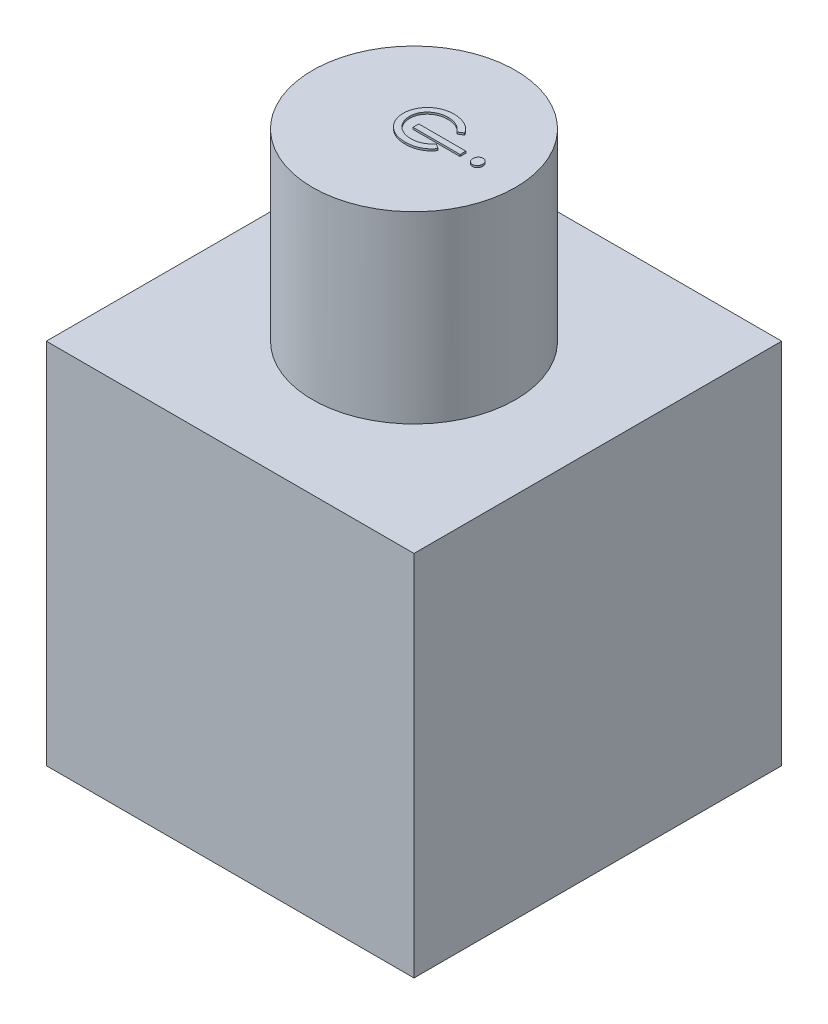
SolidWorks part; units mm, degrees
ref_plane "Front Plane" through (0, 0, 0) normal (0, 0, 1) x (1, 0, 0)
ref_plane "Top Plane" through (0, 0, 0) normal (0, 1, 0) x (1, 0, 0)
ref_plane "Right Plane" through (0, 0, 0) normal (1, 0, 0) x (0, 0, -1)
sketch "Sketch1" plane through (0, 0, 0) normal (0, 0, 1) x (1, 0, 0)
  line L1 (0, 0) -> (-20, 0)
  line L2 (0, 0) -> (0, 20)
  line L3 (0, 20) -> (-20, 20)
  line L4 (-20, 0) -> (-20, 20)
  dimension "D1" = 20
  dimension "D2" = 20
extrude "Boss-Extrude1" add sketch "Sketch1" along normal blind 20
sketch "Sketch2" plane through (0, 0, 0) normal (0, 1, 0) x (1, 0, 0)
  line L0 (-20, -10) -> (-0.3112, -10) construction
  line L1 (-20, -20) -> (-20, 0) construction
  line L2 (-10, 0) -> (-10, -20) construction
  line L5 (0, 0) -> (-20, 0) construction
  line L6 (0, -20) -> (-20, -20) construction
  circle A0 centre (-10, -10) radius 5.5208
extrude "Boss-Extrude3" add sketch "Sketch2" along normal blind 30
sketch "Sketch3" plane through (0, 30, 0) normal (0, 1, 0) x (1, 0, 0)
  text T0 " c"
extrude "Boss-Extrude4" add sketch "Sketch3" along normal blind 0.1
sketch "Sketch4" plane through (0, 30, 0) normal (0, 1, 0) x (1, 0, 0)
  line L0 (-20, -10) -> (-19.9999, -10) construction
  line L2 (-20, -20) -> (-20, 0) construction
  line L4 (0, 0) -> (-20, 0) construction
  line L5 (-10, 0) -> (-10, -19.0905) construction
  text T0 "       i"
extrude "Boss-Extrude5" add sketch "Sketch4" along normal blind 0.1
